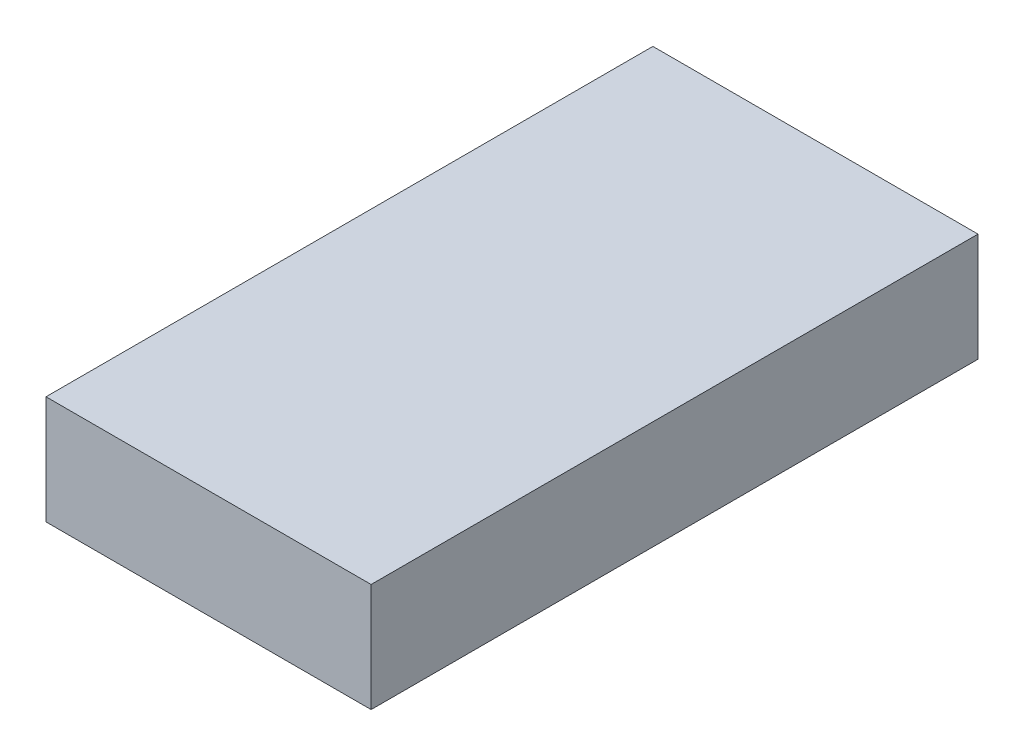
SolidWorks part; units mm, degrees
ref_plane "前视基准面" through (0, 0, 0) normal (0, 0, 1) x (1, 0, 0)
ref_plane "上视基准面" through (0, 0, 0) normal (0, 1, 0) x (1, 0, 0)
ref_plane "右视基准面" through (0, 0, 0) normal (1, 0, 0) x (0, 0, -1)
sketch "草图1" plane through (0, 0, 0) normal (0, 0, 1) x (1, 0, 0)
  line L0 (-13, -3) -> (-13, 3)
  line L1 (-15, -5) -> (15, -5)
  line L2 (-15, -5) -> (-15, 5)
  line L3 (-15, 5) -> (15, 5)
  line L4 (15, -5) -> (15, 5)
  line L5 (-15, -5) -> (15, 5) construction
  line L6 (-15, 5) -> (15, -5) construction
  line L7 (-13, 3) -> (-1.5, 3)
  line L8 (13, -3) -> (13, 3)
  line L9 (-13, -3) -> (-1.5, -3)
  line L10 (0, 7.183) -> (0, -6.8853) construction
  line L11 (-1.5, 7.183) -> (-1.5, -6.8853)
  line L12 (1.5, 7.183) -> (1.5, -6.8853)
  line L13 (-1.5, 3) -> (-1.5, -3)
  line L14 (1.5, 3) -> (1.5, -3)
  line L15 (1.5, 3) -> (13, 3)
  line L16 (-13, 3) -> (13, 3) construction
  line L17 (1.5, -3) -> (13, -3)
  line L18 (-13, -3) -> (13, -3) construction
  point P0 (0, 0)
  dimension "D1" = 2
  dimension "D2" = 1.5
  dimension "D3" = 1.5
extrude "凸台-拉伸1" add sketch "草图1" along normal blind 50 contours L11 L3 L2 L1 L9 L0 L7 | L12 L3 L11 L1 | L17 L12 L1 L4 L3 L15 L8
sketch "草图4" plane through (-15, 0, 0) normal (-1, 0, 0) x (0, 0, 1)
  line L0 (41.2851, 5) -> (41.2851, -5)
  line L1 (50, 5) -> (0, 5) construction
  line L2 (50, -5) -> (0, -5) construction
sketch "草图5" plane through (0, -5, 0) normal (0, -1, 0) x (1, 0, 0)
  line L0 (-15, 41.3607) -> (15, 41.3607)
  line L1 (-15, 50) -> (-15, 0) construction
  line L2 (15, 50) -> (15, 0) construction
  line L3 (-9.7072, 50) -> (-9.7072, 28.3093)
  line L4 (-15, 50) -> (15, 50) construction
sketch "草图6" plane through (0, 5, 0) normal (0, 1, 0) x (1, 0, 0)
  line L0 (-15, -41.3607) -> (15, -41.3607)
  line L1 (-9.7072, -28.3093) -> (-9.7072, -50)
sketch "草图7" plane through (0, -5, 0) normal (0, -1, 0) x (1, 0, 0)
  line L0 (-15, 5) -> (15, 5) construction
  line L1 (-15, 50) -> (-15, 0) construction
  line L2 (15, 50) -> (15, 0) construction
  line L3 (-15, 0) -> (15, 0) construction
  line L5 (-15, 5) -> (15, 5)
  line L6 (-15, 5) -> (-15, 6.1444)
  line L7 (-15, 6.1444) -> (15, 6.1444)
  line L8 (15, 5) -> (15, 6.1444)
  dimension "D1" = 5
sketch "草图12" plane through (0, 0, 0) normal (0, 0, -1) x (-1, 0, 0)
  line L0 (15, 5) -> (15, -5) construction
  line L1 (-15, -5) -> (15, -5)
  line L2 (-15, -5) -> (-15, -3)
  line L3 (-15, -4) -> (15, -4)
  line L4 (15, -5) -> (15, -3)
  line L5 (-15, -3) -> (15, -3)
  dimension "D1" = 1
sketch "草图13" plane through (0, 0, 0) normal (0, 0, -1) x (-1, 0, 0)
  line L0 (15, -5) -> (-15, -5) construction
  line L1 (-15, 5) -> (-14, 5)
  line L2 (-15, 5) -> (-15, -5)
  line L3 (-15, -5) -> (-14, -5)
  line L4 (-14, 5) -> (-14, -5)
  line L6 (0, 0) -> (0, 7.4092) construction
  line L7 (15, -5) -> (14, -5)
  line L8 (14, 5) -> (14, -5)
  line L9 (15, 5) -> (15, -5)
  line L10 (15, 5) -> (14, 5)
  dimension "D1" = 1
sketch "草图18" plane through (0, -5, 0) normal (0, -1, 0) x (1, 0, 0)
  line L0 (0, 50) -> (0, 0)
  line L1 (-15, 50) -> (15, 50) construction
  line L2 (0, 25) -> (15, 25)
  line L3 (15, 50) -> (15, 0) construction
  line L4 (-15, 25) -> (15, 25)
  line L5 (-15, 50) -> (-15, 0) construction
  line L6 (15, 25) -> (-15, 25)
sketch "草图19" plane through (0, 5, 0) normal (0, 1, 0) x (1, 0, 0)
  line L0 (-15, -25) -> (15, -25)
  line L1 (0, 0) -> (0, -50)
sketch "草图20" plane through (0, 0, 0) normal (0, 0, -1) x (-1, 0, 0)
  line L1 (-15, 5) -> (15, 5)
  line L2 (-15, 5) -> (-15, -5)
  line L3 (-15, -5) -> (15, -5)
  line L4 (15, 5) -> (15, -5)
extrude "凸台-拉伸2" add sketch "草图20" along normal blind 3
sketch "草图21" plane through (0, 0, 50) normal (0, 0, 1) x (1, 0, 0)
  line L1 (-15, 5) -> (15, 5)
  line L2 (-15, 5) -> (-15, -5)
  line L3 (-15, -5) -> (15, -5)
  line L4 (15, 5) -> (15, -5)
extrude "凸台-拉伸3" add sketch "草图21" along normal blind 3
